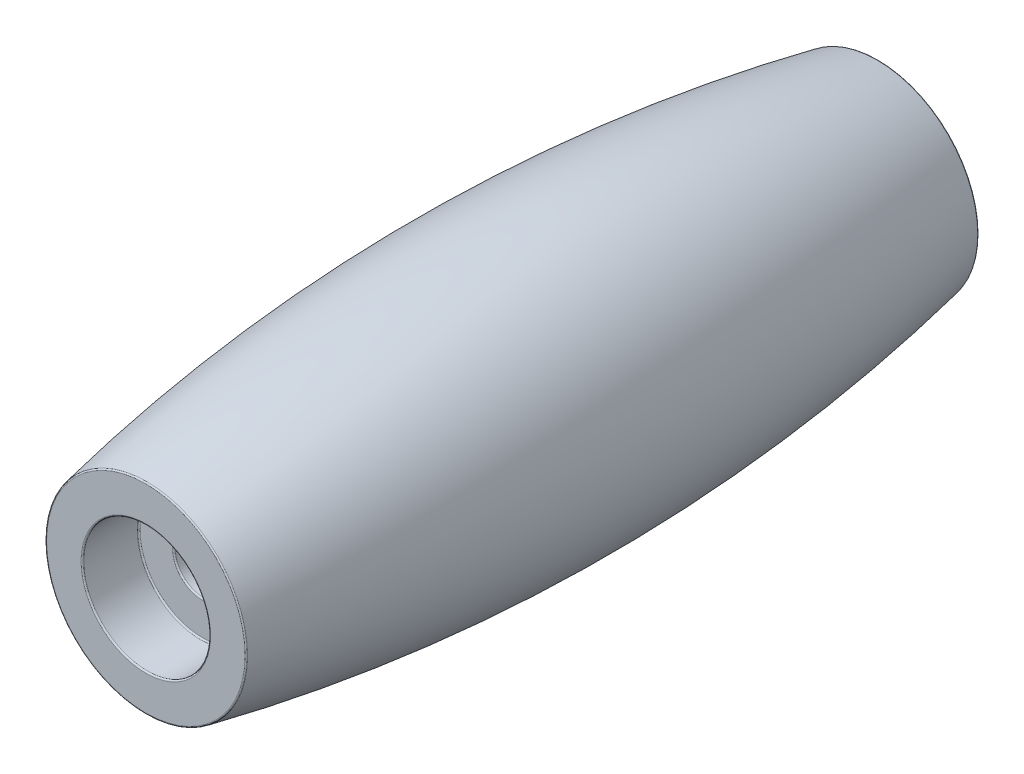
SolidWorks part; units mm, degrees
material "BUTYL"
ref_plane "Front Plane" through (0, 0, 0) normal (0, 0, 1) x (1, 0, 0)
ref_plane "Top Plane" through (0, 0, 0) normal (0, 1, 0) x (1, 0, 0)
ref_plane "Right Plane" through (0, 0, 0) normal (1, 0, 0) x (0, 0, -1)
sketch "Sketch1" plane through (0, 0, 0) normal (0, 1, 0) x (1, 0, 0)
  line L0 (0, 26) -> (0, -26) construction
  line L1 (9.725, 26) -> (9.725, -26) construction
  line L2 (0, 0) -> (9.725, 0) construction
  line L3 (2, 22) -> (2, -22)
  line L4 (4.5, 26) -> (4.5, -26) construction
  line L5 (2, 22) -> (4.5, 22)
  line L6 (4.5, 22) -> (4.5, 26)
  line L7 (2, -22) -> (4.5, -22)
  line L8 (4.5, -22) -> (4.5, -26)
  line L9 (7.125, 26) -> (7.125, -26) construction
  line L10 (4.5, 26) -> (7.125, 26)
  line L11 (4.5, -26) -> (7.125, -26)
  arc A0 (7.125, 26) -> (7.125, -26) centre (-121.575, 0) cw
  point P2 (0, 0)
  point P10 (2, 0)
  point P13 (4.5, 0)
  point P18 (7.125, 0)
  dimension "D1" = 52
  dimension "D2" = 9.725
  dimension "D3" = 4
  dimension "D4" = 4.5
  dimension "D5" = 4
  dimension "D6" = 7.125
revolve "Revolve1" add sketch "Sketch1" angle 360 about L0
fillet "Fillet1" radius 0.1 8 edges at (-2, 0, -22) (-4.5, 0, -22) (-4.5, 0, -26) (-7.125, 0, -26) (-2, 0, 22) (-4.5, 0, 22) (-4.5, 0, 26) (-7.125, 0, 26)
